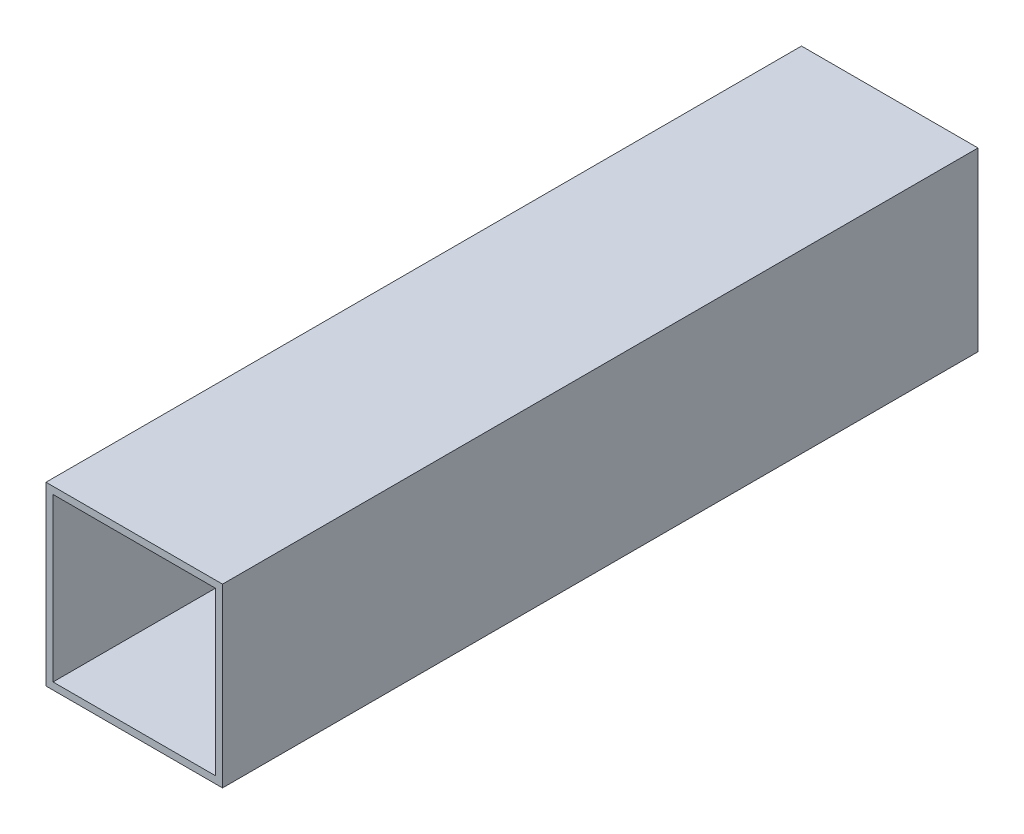
SolidWorks part; units mm, degrees
ref_plane "Front Plane" through (0, 0, 0) normal (0, 0, 1) x (1, 0, 0)
ref_plane "Top Plane" through (0, 0, 0) normal (0, 1, 0) x (1, 0, 0)
ref_plane "Right Plane" through (0, 0, 0) normal (1, 0, 0) x (0, 0, -1)
sketch "Sketch1" plane through (0, 0, 0) normal (0, 0, 1) x (1, 0, 0)
  line L1 (-25, -25) -> (25, -25)
  line L2 (-25, -25) -> (-25, 25)
  line L3 (-25, 25) -> (25, 25)
  line L4 (25, -25) -> (25, 25)
  line L5 (-25, -25) -> (25, 25) construction
  line L6 (-25, 25) -> (25, -25) construction
  line L7 (-23, -23) -> (23, -23)
  line L8 (-23, -23) -> (-23, 23)
  line L9 (-23, 23) -> (23, 23)
  line L10 (23, -23) -> (23, 23)
  line L11 (-23, -23) -> (23, 23) construction
  line L12 (-23, 23) -> (23, -23) construction
  point P0 (0, 0)
  point P6 (0, 0)
  dimension "D1" = 50
  dimension "D2" = 46
extrude "Boss-Extrude1" add sketch "Sketch1" along normal blind 214
